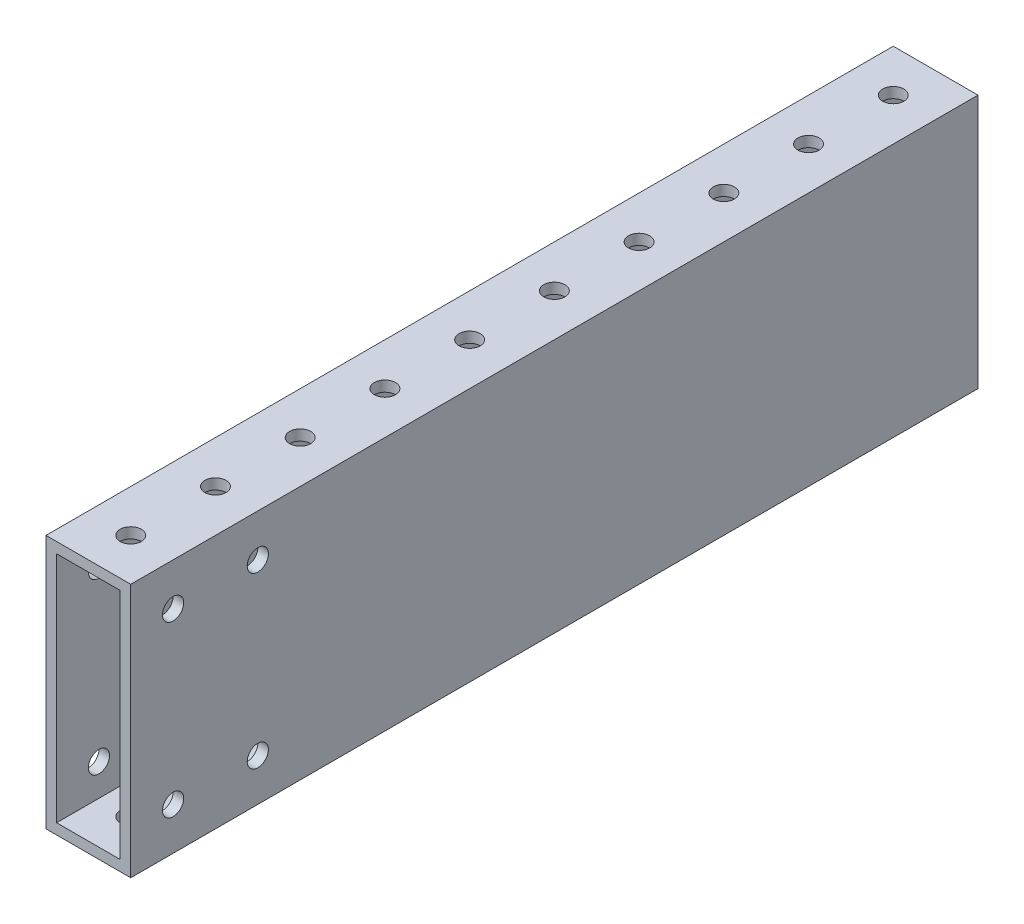
SolidWorks part; units mm, degrees
ref_plane "Front Plane" through (0, 0, 0) normal (0, 0, 1) x (1, 0, 0)
ref_plane "Top Plane" through (0, 0, 0) normal (0, 1, 0) x (1, 0, 0)
ref_plane "Right Plane" through (0, 0, 0) normal (1, 0, 0) x (0, 0, -1)
sketch "Sketch1" plane through (0, 0, 0) normal (0, 0, 1) x (1, 0, 0)
  line L1 (12.7, -38.1) -> (-12.7, -38.1)
  line L2 (12.7, -38.1) -> (12.7, 38.1)
  line L3 (12.7, 38.1) -> (-12.7, 38.1)
  line L4 (-12.7, -38.1) -> (-12.7, 38.1)
  line L5 (12.7, -38.1) -> (-12.7, 38.1) construction
  line L6 (12.7, 38.1) -> (-12.7, -38.1) construction
  line L7 (9.525, -34.925) -> (-9.525, -34.925)
  line L8 (9.525, -34.925) -> (9.525, 34.925)
  line L9 (9.525, 34.925) -> (-9.525, 34.925)
  line L10 (-9.525, -34.925) -> (-9.525, 34.925)
  line L11 (9.525, -34.925) -> (-9.525, 34.925) construction
  line L12 (9.525, 34.925) -> (-9.525, -34.925) construction
  point P0 (0, 0)
  point P6 (0, 0)
  dimension "D1" = 25.4
  dimension "D2" = 76.2
  dimension "D3" = 3.175
  dimension "D4" = 3.175
extrude "Boss-Extrude3" add sketch "Sketch1" along normal blind 254
ref_plane "Plane1" through (12.7, 38.1, 0) normal (0, 0, -1) x (-1, 0, 0)
sketch "Sketch6" plane through (0, -38.1, 0) normal (0, -1, 0) x (-1, 0, 0)
  line L0 (-12.7, -254) -> (-12.7, 0) construction
  line L1 (12.7, 0) -> (-12.7, 0) construction
  line L2 (12.7, -254) -> (12.7, 0) construction
  line L3 (12.7, -254) -> (-12.7, -254) construction
  circle A0 centre (0, -12.7) radius 3.175
  circle A1 centre (0, -38.1) radius 3.175
  circle A2 centre (0, -241.3) radius 3.175
  circle A3 centre (0, -215.9) radius 3.175
  dimension "D1" = 6.35
  dimension "D2" = 6.35
  dimension "D6" = 12.7
  dimension "D7" = 6.35
  dimension "D8" = 6.35
  dimension "D9" = 12.7
  dimension "D10" = 12.7
  dimension "D12" = 12.7
  dimension "D3" = 12.7
  dimension "D4" = 25.4
  dimension "D5" = 12.7
  dimension "D11" = 25.4
extrude "Cut-Extrude1" cut sketch "Sketch6" against normal blind 806.45
sketch "Sketch7" plane through (0, -38.1, 0) normal (0, -1, 0) x (-1, 0, 0)
  line L0 (-12.7, -254) -> (-12.7, 0) construction
  line L1 (12.7, -254) -> (12.7, 0) construction
  circle A0 centre (0, -88.9) radius 3.175
  circle A1 centre (0, -38.1) radius 3.175 construction
  circle A2 centre (0, -114.3) radius 3.175
  circle A3 centre (0, -165.1) radius 3.175
  circle A4 centre (0, -215.9) radius 3.175 construction
  circle A5 centre (0, -139.7) radius 3.175
  dimension "D1" = 50.8
  dimension "D2" = 6.35
  dimension "D3" = 12.7
  dimension "D4" = 25.4
  dimension "D5" = 6.35
  dimension "D6" = 12.7
  dimension "D7" = 50.8
  dimension "D8" = 6.35
  dimension "D9" = 12.7
  dimension "D10" = 6.35
  dimension "D11" = 12.7
  dimension "D12" = 25.4
extrude "Cut-Extrude2" cut sketch "Sketch7" against normal through all both and the other way through all
sketch "Sketch8" plane through (0, -38.1, 0) normal (0, -1, 0) x (-1, 0, 0)
  line L0 (-12.7, -254) -> (-12.7, 0) construction
  line L1 (12.7, -254) -> (12.7, 0) construction
  circle A0 centre (0, -190.5) radius 3.175
  circle A1 centre (0, -114.3) radius 3.175 construction
  circle A2 centre (0, -215.9) radius 3.175
  circle A3 centre (0, -63.5) radius 3.175
  circle A4 centre (0, -139.7) radius 3.175 construction
  circle A5 centre (0, -38.1) radius 3.175
  dimension "D1" = 6.35
  dimension "D2" = 12.7
  dimension "D3" = 76.2
  dimension "D4" = 6.35
  dimension "D5" = 25.4
  dimension "D6" = 12.7
  dimension "D7" = 76.2
  dimension "D8" = 6.35
  dimension "D9" = 12.7
  dimension "D10" = 25.4
  dimension "D11" = 6.35
  dimension "D12" = 12.7
extrude "Cut-Extrude4" cut sketch "Sketch8" against normal through all both and the other way through all contours A0 | A2 | A3 | A5
sketch "Sketch11" plane through (12.7, 0, 0) normal (1, 0, 0) x (0, 0, -1)
  line L0 (-254, 38.1) -> (0, 38.1) construction
  line L2 (-254, -38.1) -> (-254, 38.1) construction
  line L3 (-254, -38.1) -> (0, -38.1) construction
  circle A4 centre (-241.3, -25.4) radius 3.175
  circle A5 centre (-215.9, -25.4) radius 3.175
  circle A6 centre (-215.9, 25.4) radius 3.175
  circle A7 centre (-241.3, 25.4) radius 3.175
  dimension "D13" = 12.7
  dimension "D14" = 12.7
  dimension "D15" = 12.7
  dimension "D16" = 12.7
  dimension "D17" = 6.35
  dimension "D18" = 6.35
  dimension "D19" = 6.35
  dimension "D20" = 6.35
  dimension "D21" = 12.7
  dimension "D22" = 25.4
  dimension "D23" = 25.4
  dimension "D24" = 12.7
extrude "Cut-Extrude6" cut sketch "Sketch11" against normal through all both
